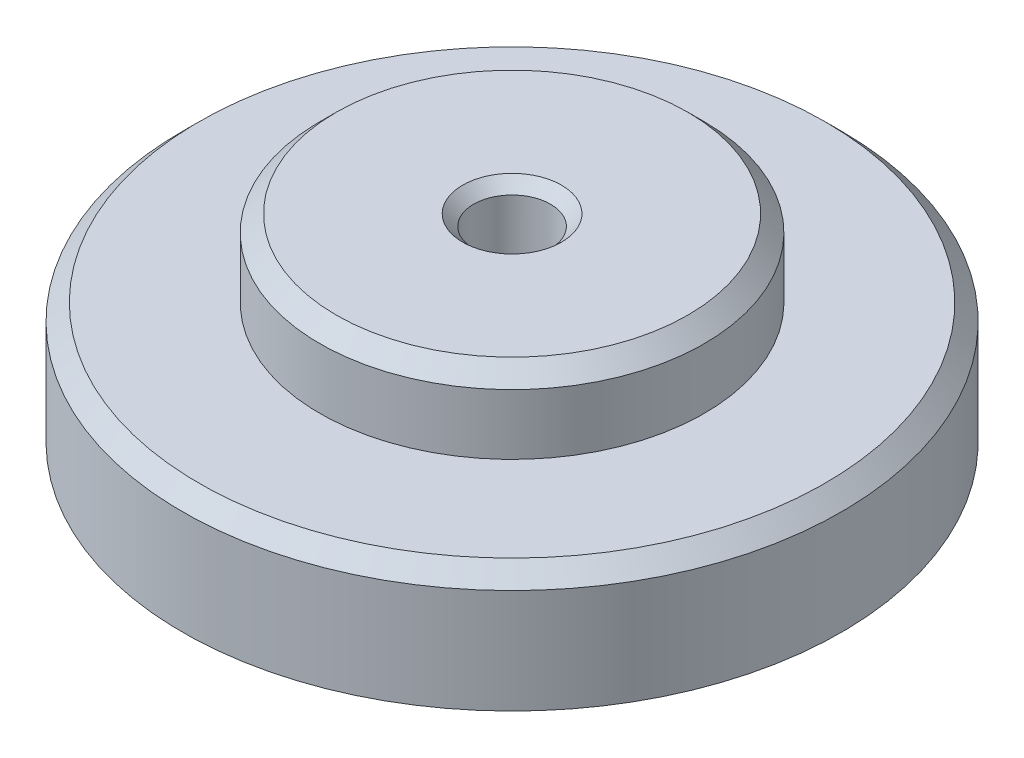
SolidWorks part; units mm, degrees
ref_plane "Front Plane" through (0, 0, 0) normal (0, 0, 1) x (1, 0, 0)
ref_plane "Top Plane" through (0, 0, 0) normal (0, 1, 0) x (1, 0, 0)
ref_plane "Right Plane" through (0, 0, 0) normal (1, 0, 0) x (0, 0, -1)
sketch "Sketch1" plane through (0, 0, 0) normal (0, 0, 1) x (1, 0, 0)
  line L0 (0, 0) -> (0, 36)
  line L1 (0, 36) -> (32, 36)
  line L2 (35, 33) -> (35, 22)
  line L3 (35, 22) -> (57, 22)
  line L4 (60, 19) -> (60, 0)
  line L5 (60, 0) -> (45, 0)
  line L7 (45, 11) -> (0, 11)
  line L9 (45, 0) -> (45, 11)
  line L11 (60, 0) -> (0, 0) construction
  line L12 (60, 11) -> (0, 11) construction
  line L13 (32, 36) -> (35, 33)
  line L14 (57, 22) -> (60, 19)
  point P3 (35, 36)
  point P5 (60, 22)
revolve "Revolve1" add sketch "Sketch1" angle 360 about L0
hole_wizard "M16 Tapped Hole1" positions "Sketch2" profile "Sketch3" tap size "M16" standard "ISO"
sketch "Sketch2" plane through (0, 36, 0) normal (0, 1, 0) x (1, 0, 0)
  point P0 (0, 0)
sketch "Sketch3" plane through (0, 36, 0) normal (1, 0, 0) x (0, 0, 1)
  line L0 (0, 0) -> (0, 42)
  line L1 (0, 42) -> (7, 42)
  line L2 (7, 42) -> (7, 0)
  line L5 (7, 0) -> (0, 0)
  line L10 (0, 42) -> (-7, 42) construction
  line L11 (0, -6.35) -> (0, 107.95) construction
  dimension "Tap Drill Dia." = 14
  dimension "Tap Drill Depth" = 42
  dimension "Drill Angle" = 180
cosmetic thread "Hole Thread1" parameters "D1"=32, "D2"=16
chamfer "Chamfer1" distance 2 angle 45 1 edges at (0, 36, 7)
